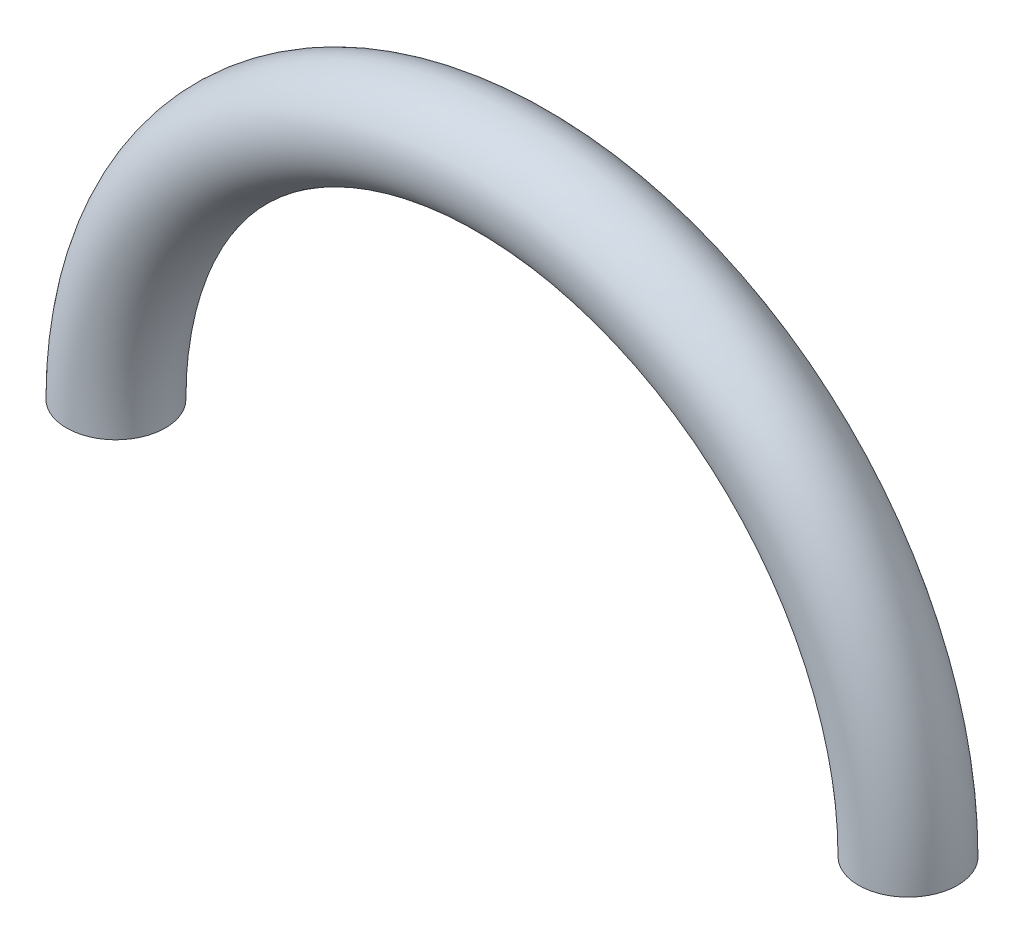
SolidWorks part; units mm, degrees
material "Plain Carbon Steel"
ref_plane "Front Plane" through (0, 0, 0) normal (0, 0, 1) x (1, 0, 0)
ref_plane "Top Plane" through (0, 0, 0) normal (0, 1, 0) x (1, 0, 0)
ref_plane "Right Plane" through (0, 0, 0) normal (1, 0, 0) x (0, 0, -1)
sketch "Sketch1" plane through (0, 0, 0) normal (0, 1, 0) x (1, 0, 0)
  line L0 (0, -6.35) -> (0, 6.35) construction
  line L2 (25.4, 0) -> (0, 0)
  circle A0 centre (25.4, 0) radius 3.175
  point P5 (-25.4, 0)
revolve "ring" add sketch "Sketch1" angle 180 about L0
